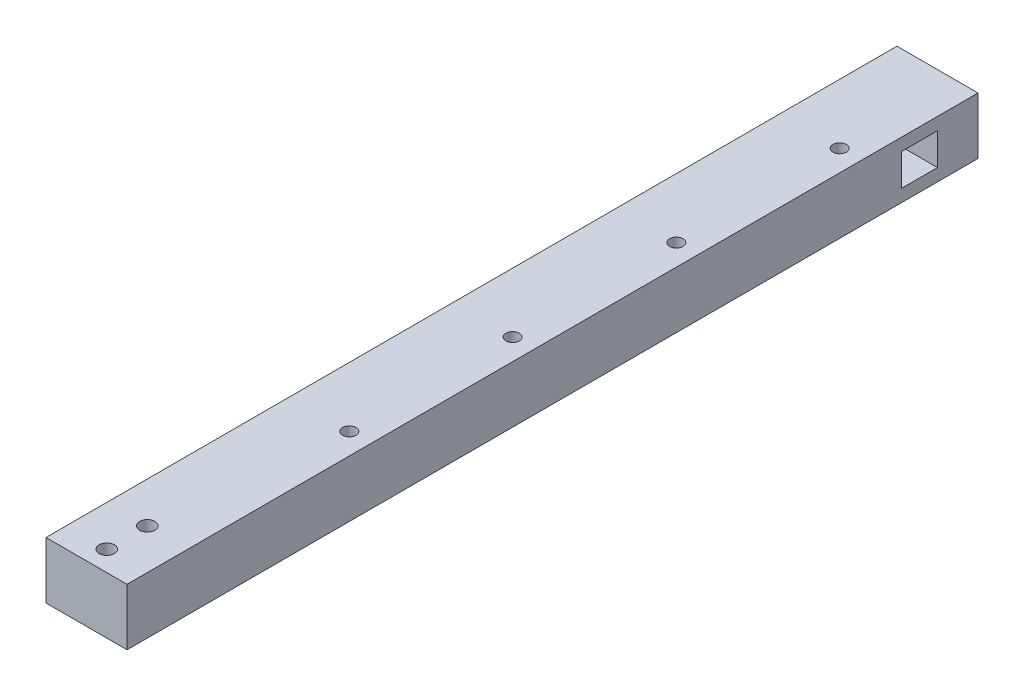
SolidWorks part; units mm, degrees
ref_plane "Front Plane" through (0, 0, 0) normal (0, 0, 1) x (1, 0, 0)
ref_plane "Top Plane" through (0, 0, 0) normal (0, 1, 0) x (1, 0, 0)
ref_plane "Right Plane" through (0, 0, 0) normal (1, 0, 0) x (0, 0, -1)
sketch "Sketch1" plane through (0, 0, 0) normal (0, 1, 0) x (1, 0, 0)
  line L1 (-6.35, -66.675) -> (6.35, -66.675)
  line L2 (-6.35, -66.675) -> (-6.35, 66.675)
  line L3 (-6.35, 66.675) -> (6.35, 66.675)
  line L4 (6.35, -66.675) -> (6.35, 66.675)
  line L5 (-6.35, -66.675) -> (6.35, 66.675) construction
  line L6 (-6.35, 66.675) -> (6.35, -66.675) construction
  point P0 (0, 0)
  dimension "D1" = 12.7
  dimension "D2" = 133.35
extrude "Boss-Extrude1" add sketch "Sketch1" along normal mid plane 8.89
sketch "Sketch2" plane through (0, -4.445, 0) normal (0, -1, 0) x (1, 0, 0)
  line L0 (-6.35, 66.675) -> (6.35, 66.675) construction
  circle A0 centre (0, 57.15) radius 1.2
  circle A1 centre (0, 63.5) radius 1.2
  point P4 (0, 0)
  point P6 (0, 0)
  point P9 (0, 0)
  point P10 (0, 0)
  dimension "D2" = 2.4
  dimension "D1" = 3.175
  dimension "D3" = 6.35
extrude "Cut-Extrude1" cut sketch "Sketch2" against normal through all both and the other way through all
sketch "Sketch3" plane through (0, 0, -66.675) normal (0, 0, -1) x (-1, 0, 0)
  circle A0 centre (0, 0) radius 1.2
  dimension "D1" = 2.4
extrude "Cut-Extrude2" cut sketch "Sketch3" against normal blind 12
sketch "Sketch4" plane through (6.35, 0, 0) normal (1, 0, 0) x (0, 0, -1)
  line L0 (66.675, 4.445) -> (66.675, -4.445) construction
  line L5 (54.675, -1.2) -> (54.675, 1.2) construction
  line L6 (54.675, 2.5) -> (60.325, 2.5)
  line L7 (54.675, 2.5) -> (54.675, -2.5)
  line L8 (54.675, -2.5) -> (60.325, -2.5)
  line L9 (60.325, 2.5) -> (60.325, -2.5)
  line L10 (54.675, 2.5) -> (60.325, -2.5) construction
  line L11 (54.675, -2.5) -> (60.325, 2.5) construction
  line L12 (54.675, -1.2) -> (54.675, 1.2) construction
  point P0 (57.5, 0)
  point P5 (0, 0)
  dimension "D1" = 6.35
  dimension "D2" = 5
extrude "Cut-Extrude3" cut sketch "Sketch4" against normal through all
sketch "Sketch5" plane through (0, -4.445, 0) normal (0, -1, 0) x (1, 0, 0)
  circle A0 centre (3.0157, -48.3315) radius 1.0543 construction
  circle A1 centre (3.0157, -22.739) radius 1.0543 construction
  circle A2 centre (3.0157, 2.9185) radius 1.0543 construction
  circle A3 centre (3.0157, 28.511) radius 1.0543 construction
  circle A4 centre (3.0157, -48.3315) radius 1.0543
  circle A5 centre (3.0157, -22.739) radius 1.0543
  circle A6 centre (3.0157, 2.9185) radius 1.0543
  circle A7 centre (3.0157, 28.511) radius 1.0543
extrude "Cut-Extrude4" cut sketch "Sketch5" against normal through all
